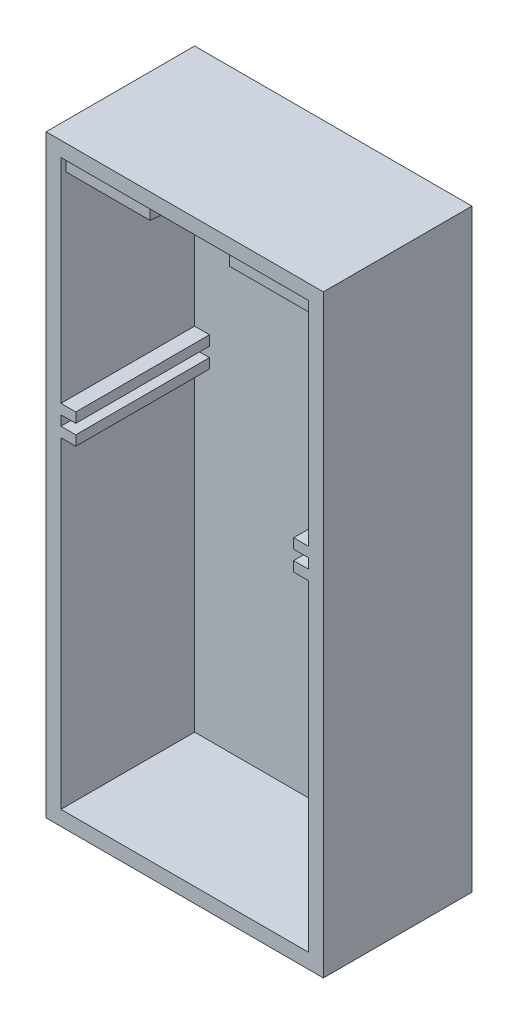
SolidWorks part; units mm, degrees
ref_plane "Front Plane" through (0, 0, 0) normal (0, 0, 1) x (1, 0, 0)
ref_plane "Top Plane" through (0, 0, 0) normal (0, 1, 0) x (1, 0, 0)
ref_plane "Right Plane" through (0, 0, 0) normal (1, 0, 0) x (0, 0, -1)
sketch "Sketch1" plane through (0, 0, 0) normal (0, 0, 1) x (1, 0, 0)
  line L1 (0, 0) -> (-56, 0)
  line L2 (0, 0) -> (0, 120)
  line L3 (0, 120) -> (-56, 120)
  line L4 (-56, 0) -> (-56, 120)
  dimension "D1" = 56
  dimension "D2" = 120
extrude "Boss-Extrude1" add sketch "Sketch1" along normal blind 30
shell "Shell1" thickness 3
sketch "Sketch2" plane through (0, 0, 3) normal (0, 0, 1) x (1, 0, 0)
  line L0 (-53, 117) -> (-53, 3) construction
  line L1 (-53, 117) -> (-3, 117)
  line L2 (-53, 117) -> (-53, 114)
  line L3 (-53, 114) -> (-3, 114)
  line L4 (-3, 117) -> (-3, 114)
  line L5 (-3, 3) -> (-3, 117) construction
  line L7 (-3, 117) -> (-53, 117) construction
  dimension "D1" = 3
  dimension "D2" = 0
extrude "Boss-Extrude2" add sketch "Sketch2" along normal blind 26
sketch "Sketch3" plane through (0, 114, 0) normal (0, -1, 0) x (1, 0, 0)
  line L0 (-53, 29) -> (-3, 29) construction
  line L1 (-36, 29) -> (-20, 29)
  arc A0 (-20, 29) -> (-36, 29) centre (-28, 29) cw
  dimension "D1" = 8
extrude "Cut-Extrude5" cut sketch "Sketch3" against normal blind 3
sketch "Sketch6" plane through (-53, 0, 0) normal (1, 0, 0) x (0, 0, -1)
  line L0 (-30, 0) -> (-30, 120) construction
  line L1 (-30, 74) -> (0, 74)
  line L2 (-30, 74) -> (-30, 72)
  line L3 (-30, 72) -> (0, 72)
  line L4 (0, 74) -> (0, 72)
  line L5 (0, 0) -> (0, 120) construction
  line L8 (-30, 120) -> (0, 120) construction
  dimension "D1" = 2
  dimension "D2" = 46
extrude "Boss-Extrude3" add sketch "Sketch6" along normal blind 3
sketch "Sketch7" plane through (-53, 0, 0) normal (1, 0, 0) x (0, 0, -1)
  line L0 (-30, 0) -> (-30, 120) construction
  line L1 (-30, 70) -> (0, 70)
  line L2 (-30, 70) -> (-30, 68)
  line L3 (-30, 68) -> (0, 68)
  line L4 (0, 70) -> (0, 68)
  line L5 (0, 0) -> (0, 120) construction
  line L6 (-30, 72) -> (-3, 72) construction
  dimension "D1" = 2
  dimension "D2" = 2
extrude "Boss-Extrude4" add sketch "Sketch7" along normal blind 3
ref_plane "Plane1" through (-28, 0, 0) normal (1, 0, 0) x (0, 0, -1)
mirror "Mirror1" about plane through (-28, 0, 0) normal (1, 0, 0) of "Boss-Extrude4", "Boss-Extrude3"
